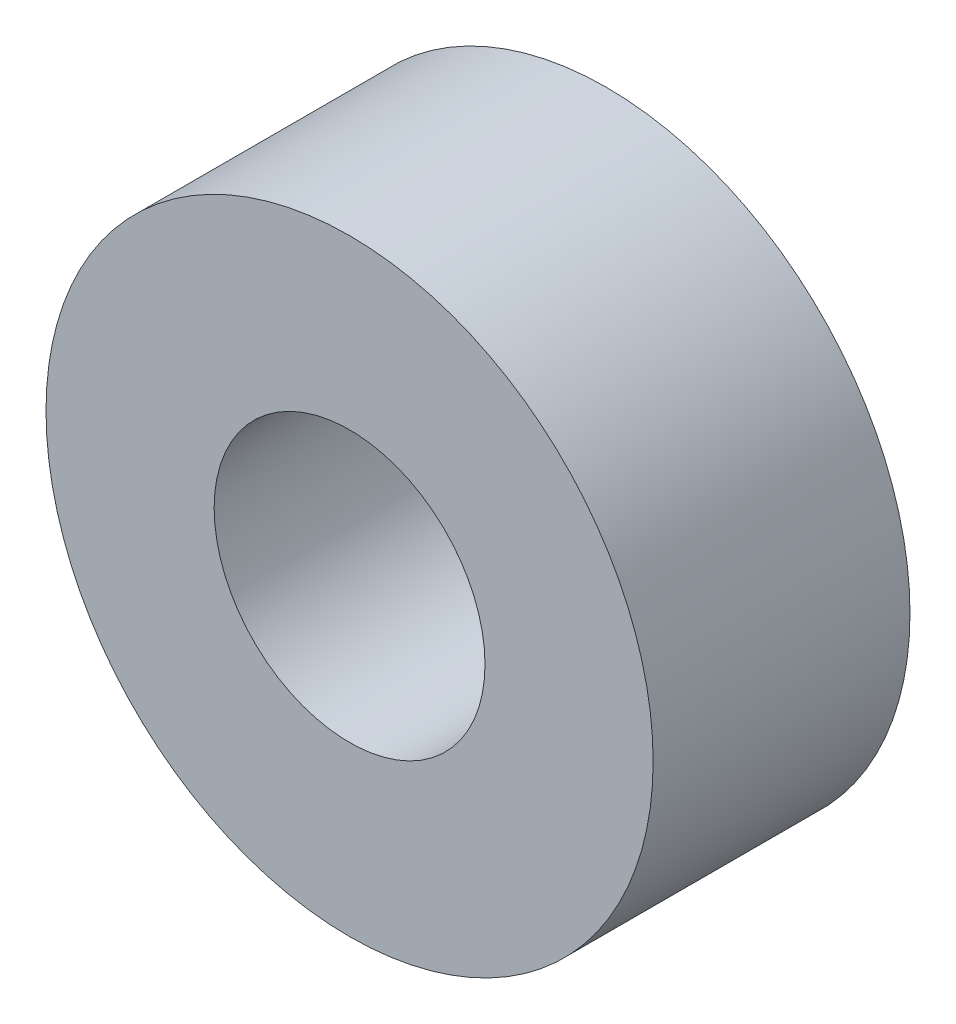
SolidWorks part; units mm, degrees
ref_plane "Front Plane" through (0, 0, 0) normal (0, 0, 1) x (1, 0, 0)
ref_plane "Top Plane" through (0, 0, 0) normal (0, 1, 0) x (1, 0, 0)
ref_plane "Right Plane" through (0, 0, 0) normal (1, 0, 0) x (0, 0, -1)
sketch "Sketch1" plane through (0, 0, 0) normal (0, 0, 1) x (1, 0, 0)
  circle A0 centre (0, 0) radius 2.9
  circle A1 centre (0, 0) radius 6.5
  dimension "D1" = 5.8
  dimension "D2" = 13
extrude "Boss-Extrude1" add sketch "Sketch1" along normal blind 5.5
